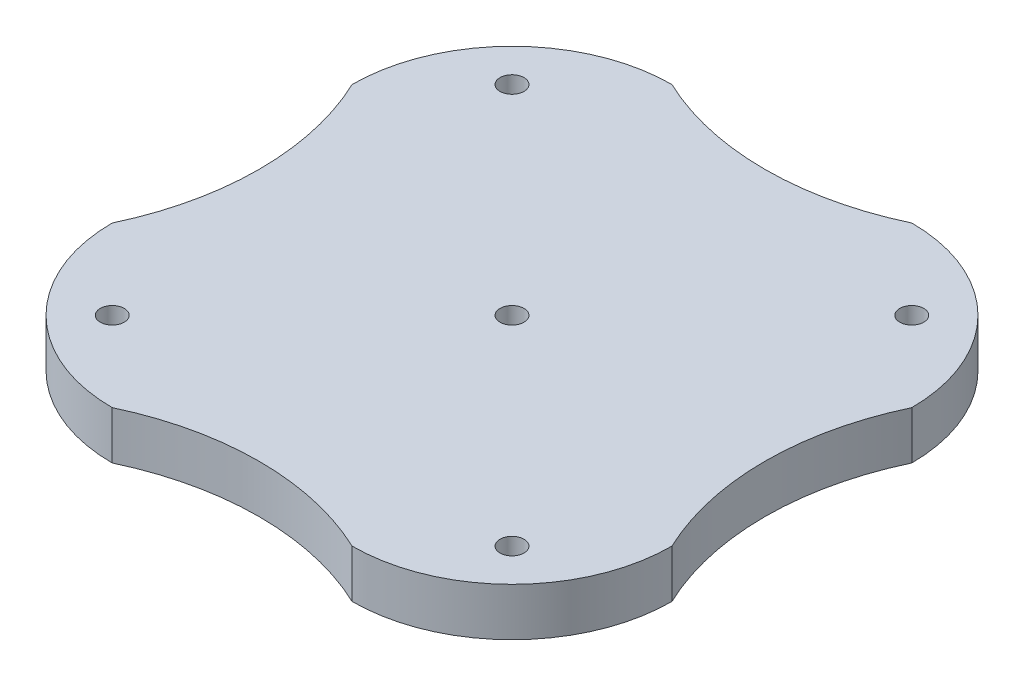
SolidWorks part; units mm, degrees
material "ABS"
ref_plane "Спереди" through (0, 0, 0) normal (0, 0, 1) x (1, 0, 0)
ref_plane "Сверху" through (0, 0, 0) normal (0, 1, 0) x (1, 0, 0)
ref_plane "Справа" through (0, 0, 0) normal (1, 0, 0) x (0, 0, -1)
sketch "Эскиз1" plane through (0, 0, 0) normal (0, 1, 0) x (1, 0, 0)
  line L1 (15, -35) -> (-15, -35)
  line L2 (35, -15) -> (35, 15)
  line L3 (15, 35) -> (-15, 35)
  line L4 (-35, -15) -> (-35, 15)
  line L5 (35, -35) -> (-35, 35) construction
  line L6 (35, 35) -> (-35, -35) construction
  arc A0 (35, 15) -> (15, 35) centre (15, 15) ccw
  arc A1 (15, -35) -> (35, -15) centre (15, -15) ccw
  arc A2 (-15, -35) -> (-35, -15) centre (-15, -15) cw
  arc A3 (-15, 35) -> (-35, 15) centre (-15, 15) ccw
  point P0 (0, 0)
  dimension "D3" = 20
  dimension "D1" = 70
  dimension "D2" = 70
extrude "Бобышка-Вытянуть1" add sketch "Эскиз1" along normal blind 6
sketch "Эскиз2" plane through (0, 0, 0) normal (0, 1, 0) x (1, 0, 0)
  line L1 (25, -25) -> (-25, -25)
  line L2 (25, -25) -> (25, 25)
  line L3 (25, 25) -> (-25, 25)
  line L4 (-25, -25) -> (-25, 25)
  line L5 (25, -25) -> (-25, 25) construction
  line L6 (25, 25) -> (-25, -25) construction
  circle A0 centre (-25, 25) radius 1.5
  circle A1 centre (25, 25) radius 1.5
  circle A2 centre (25, -25) radius 1.5
  circle A3 centre (-25, -25) radius 1.5
  circle A4 centre (0, 0) radius 1.5
  point P0 (0, 0)
  dimension "D1" = 3
  dimension "D2" = 50
  dimension "D3" = 50
extrude "Вырез-Вытянуть1" cut sketch "Эскиз2" along normal blind 6 contours A0 | A1 | A2 | A3 | A4
sketch "Эскиз3" plane through (0, 0, 0) normal (0, 1, 0) x (1, 0, 0)
  line L1 (-26.7321, 28) -> (-28.4641, 25)
  line L2 (-28.4641, 25) -> (-26.7321, 22)
  line L3 (-26.7321, 22) -> (-23.2679, 22)
  line L4 (-23.2679, 22) -> (-21.5359, 25)
  line L5 (-21.5359, 25) -> (-23.2679, 28)
  line L6 (-23.2679, 28) -> (-26.7321, 28)
  line L7 (23.2679, 28) -> (21.5359, 25)
  line L8 (21.5359, 25) -> (23.2679, 22)
  line L9 (23.2679, 22) -> (26.7321, 22)
  line L10 (26.7321, 22) -> (28.4641, 25)
  line L11 (28.4641, 25) -> (26.7321, 28)
  line L12 (26.7321, 28) -> (23.2679, 28)
  line L13 (23.2679, -22) -> (21.5359, -25)
  line L14 (21.5359, -25) -> (23.2679, -28)
  line L15 (23.2679, -28) -> (26.7321, -28)
  line L16 (26.7321, -28) -> (28.4641, -25)
  line L17 (28.4641, -25) -> (26.7321, -22)
  line L18 (26.7321, -22) -> (23.2679, -22)
  line L19 (-26.7321, -22) -> (-28.4641, -25)
  line L20 (-28.4641, -25) -> (-26.7321, -28)
  line L21 (-26.7321, -28) -> (-23.2679, -28)
  line L22 (-23.2679, -28) -> (-21.5359, -25)
  line L23 (-21.5359, -25) -> (-23.2679, -22)
  line L24 (-23.2679, -22) -> (-26.7321, -22)
  line L25 (-1.7321, 3) -> (-3.4641, 0)
  line L26 (-3.4641, 0) -> (-1.7321, -3)
  line L27 (-1.7321, -3) -> (1.7321, -3)
  line L28 (1.7321, -3) -> (3.4641, 0)
  line L29 (3.4641, 0) -> (1.7321, 3)
  line L30 (1.7321, 3) -> (-1.7321, 3)
  circle A0 centre (-25, 25) radius 3 construction
  circle A1 centre (25, 25) radius 3 construction
  circle A2 centre (25, -25) radius 3 construction
  circle A3 centre (-25, -25) radius 3 construction
  circle A4 centre (0, 0) radius 3 construction
  dimension "6" = 6
extrude "Вырез-Вытянуть2" cut sketch "Эскиз3" along normal blind 2
sketch "Эскиз4" plane through (0, 0, 0) normal (0, 1, 0) x (1, 0, 0)
  arc A0 (-35, -15) -> (-15, -35) centre (-15, -15) ccw construction
  arc A1 (15, -35) -> (35, -15) centre (15, -15) ccw construction
  arc A2 (35, 15) -> (15, 35) centre (15, 15) ccw construction
  arc A3 (-15, 35) -> (-35, 15) centre (-15, 15) ccw construction
  arc A4 (-35, -15) -> (-15, -35) centre (-15, -15) ccw
  arc A5 (15, -35) -> (35, -15) centre (15, -15) ccw
  arc A6 (35, 15) -> (15, 35) centre (15, 15) ccw
  arc A7 (-15, 35) -> (-35, 15) centre (-15, 15) ccw
  circle A8 centre (0, 66.6228) radius 35
  circle A9 centre (66.6228, 0) radius 35
  circle A10 centre (0, -66.6228) radius 35
  circle A11 centre (-66.6228, 0) radius 35
  point P23 (0, 0)
  dimension "D1" = 70
  dimension "D2" = 4
extrude "Вырез-Вытянуть3" cut sketch "Эскиз4" along normal through all contours A11 | A8 | A9 | A10
equation "\"D2@Эскиз1\"=\"D1@Эскиз1\""
equation "\"D3@Эскиз2\"=\"D2@Эскиз2\""
